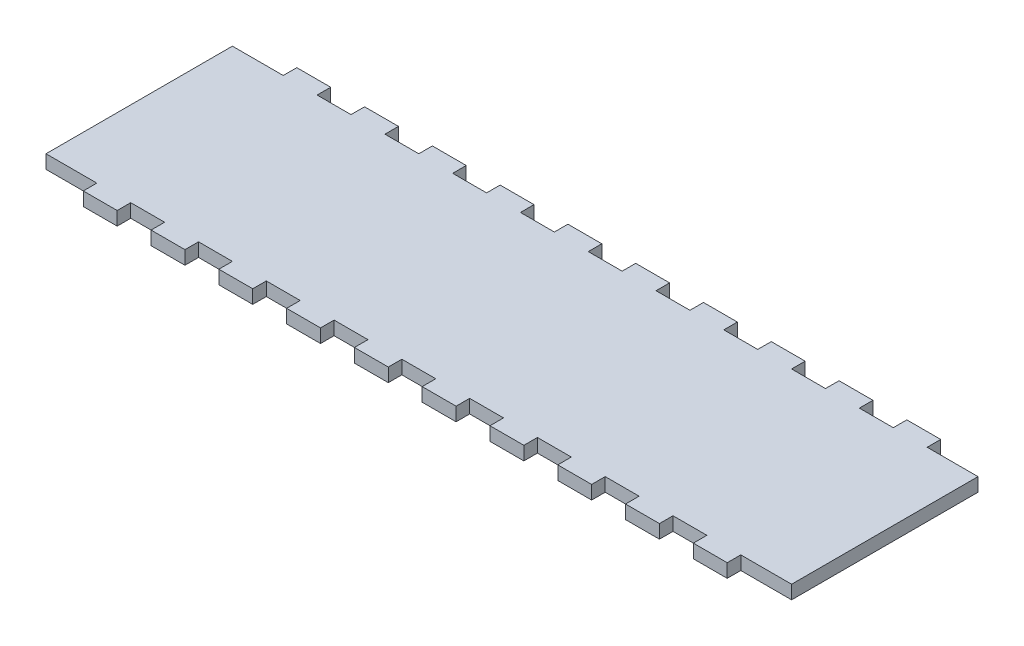
SolidWorks part; units mm, degrees
ref_plane "Спереди" through (0, 0, 0) normal (0, 0, 1) x (1, 0, 0)
ref_plane "Сверху" through (0, 0, 0) normal (0, 1, 0) x (1, 0, 0)
ref_plane "Справа" through (0, 0, 0) normal (1, 0, 0) x (0, 0, -1)
sketch "Эскиз3" plane through (0, 0, 0) normal (0, 1, 0) x (1, 0, 0)
  line L1 (-80, 29.3305) -> (-19.1885, 29.3305) construction
  line L2 (110, -32) -> (110, 23)
  line L3 (-110, 23) -> (-110, -32)
  line L4 (-95, 23) -> (-95, 27)
  line L5 (-95, 27) -> (-85, 27)
  line L6 (-85, 23) -> (-85, 27)
  line L7 (-75, 27) -> (-65, 27)
  line L8 (-75, 23) -> (-75, 27)
  line L9 (-65, 23) -> (-65, 27)
  line L10 (-55, 27) -> (-45, 27)
  line L11 (-55, 23) -> (-55, 27)
  line L12 (-45, 23) -> (-45, 27)
  line L13 (-35, 27) -> (-25, 27)
  line L14 (-35, 23) -> (-35, 27)
  line L15 (-25, 23) -> (-25, 27)
  line L16 (-15, 27) -> (-5, 27)
  line L17 (-15, 23) -> (-15, 27)
  line L18 (-5, 23) -> (-5, 27)
  line L19 (5, 27) -> (15, 27)
  line L20 (5, 23) -> (5, 27)
  line L21 (15, 23) -> (15, 27)
  line L22 (25, 27) -> (35, 27)
  line L23 (25, 23) -> (25, 27)
  line L24 (35, 23) -> (35, 27)
  line L25 (45, 27) -> (55, 27)
  line L26 (45, 23) -> (45, 27)
  line L27 (55, 23) -> (55, 27)
  line L28 (65, 27) -> (75, 27)
  line L29 (65, 23) -> (65, 27)
  line L30 (75, 23) -> (75, 27)
  line L31 (85, 27) -> (95, 27)
  line L32 (85, 23) -> (85, 27)
  line L33 (95, 23) -> (95, 27)
  line L34 (-95, 23) -> (-110, 23)
  line L35 (-85, 23) -> (-75, 23)
  line L36 (-65, 23) -> (-55, 23)
  line L37 (-45, 23) -> (-35, 23)
  line L38 (-25, 23) -> (-15, 23)
  line L39 (-5, 23) -> (5, 23)
  line L40 (45, 23) -> (35, 23)
  line L41 (25, 23) -> (15, 23)
  line L42 (65, 23) -> (55, 23)
  line L43 (85, 23) -> (75, 23)
  line L44 (95, 23) -> (110, 23)
  line L45 (-110, -4.5) -> (110, -4.5) construction
  line L56 (-95, -32) -> (-110, -32)
  line L57 (95, -32) -> (95, -36)
  line L58 (85, -32) -> (85, -36)
  line L59 (85, -36) -> (95, -36)
  line L60 (75, -32) -> (75, -36)
  line L61 (65, -32) -> (65, -36)
  line L62 (65, -36) -> (75, -36)
  line L63 (55, -32) -> (55, -36)
  line L64 (45, -32) -> (45, -36)
  line L65 (45, -36) -> (55, -36)
  line L66 (35, -32) -> (35, -36)
  line L67 (25, -32) -> (25, -36)
  line L68 (25, -36) -> (35, -36)
  line L69 (15, -32) -> (15, -36)
  line L70 (5, -32) -> (5, -36)
  line L71 (5, -36) -> (15, -36)
  line L72 (-5, -32) -> (-5, -36)
  line L73 (-15, -32) -> (-15, -36)
  line L74 (-15, -36) -> (-5, -36)
  line L75 (-25, -32) -> (-25, -36)
  line L76 (-35, -32) -> (-35, -36)
  line L77 (-35, -36) -> (-25, -36)
  line L78 (-45, -32) -> (-45, -36)
  line L79 (-55, -32) -> (-55, -36)
  line L80 (-55, -36) -> (-45, -36)
  line L81 (-65, -32) -> (-65, -36)
  line L82 (-75, -32) -> (-75, -36)
  line L83 (-75, -36) -> (-65, -36)
  line L84 (-85, -32) -> (-85, -36)
  line L85 (-95, -36) -> (-85, -36)
  line L86 (-95, -32) -> (-95, -36)
  line L87 (-85, -32) -> (-75, -32)
  line L88 (-65, -32) -> (-55, -32)
  line L89 (-45, -32) -> (-35, -32)
  line L90 (-25, -32) -> (-15, -32)
  line L91 (15, -32) -> (25, -32)
  line L92 (-5, -32) -> (5, -32)
  line L93 (35, -32) -> (45, -32)
  line L94 (55, -32) -> (65, -32)
  line L95 (75, -32) -> (85, -32)
  line L96 (95, -32) -> (110, -32)
  point P0 (-80, 29.3305)
  point P3 (-90, 25)
  point P90 (-90, -34)
  point P91 (-80, -38.3305)
  dimension "D1" = 4
  dimension "D2" = 10
  dimension "D3" = 55
  dimension "D4" = 220
  dimension "D5" = 15
extrude "Бобышка-Вытянуть2" add sketch "Эскиз3" along normal blind 4
sketch "Эскиз4" plane through (0, 0, 0) normal (0, 1, 0) x (1, 0, 0)
  line L0 (-110, 23) -> (-110, -32) construction
  line L1 (-110, -29.5) -> (110, -29.5)
  line L2 (110, -32) -> (110, 23) construction
  line L4 (-110, 20.5) -> (110, 20.5)
  line L5 (-110, -32) -> (-95, -32) construction
  line L6 (-100, -32) -> (-100, 23)
  line L10 (100, -32) -> (100, 23)
  line L11 (-95, 23) -> (-110, 23) construction
  point P2 (-110, -29.5)
  point P12 (-100, -32)
  dimension "D1" = 2.5
  dimension "D2" = 10
